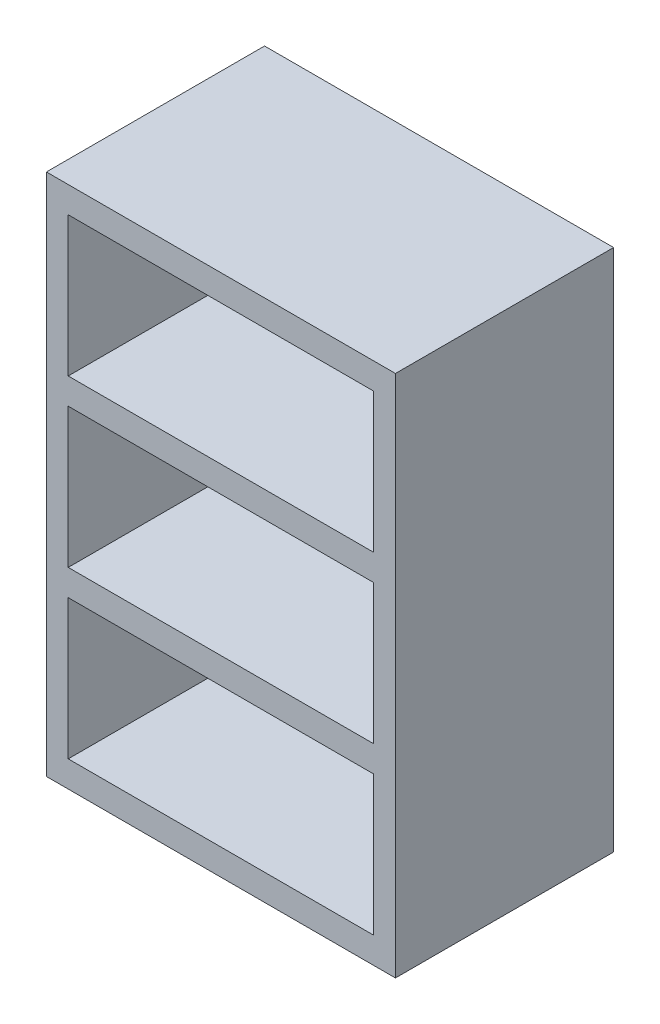
SolidWorks part; units mm, degrees
ref_plane "Front" through (0, 0, 0) normal (0, 0, 1) x (1, 0, 0)
ref_plane "Top" through (0, 0, 0) normal (0, 1, 0) x (1, 0, 0)
ref_plane "Right" through (0, 0, 0) normal (1, 0, 0) x (0, 0, -1)
sketch "Sketch1" plane through (0, 0, 0) normal (0, 0, 1) x (1, 0, 0)
  line L1 (-400, -600) -> (400, -600)
  line L2 (-400, -600) -> (-400, 600)
  line L3 (-400, 600) -> (400, 600)
  line L4 (400, -600) -> (400, 600)
  line L5 (-400, -600) -> (400, 600) construction
  line L6 (-400, 600) -> (400, -600) construction
  point P0 (0, 0)
  dimension "D1" = 1200
  dimension "D2" = 800
extrude "Boss-Extrude1" add sketch "Sketch1" along normal blind 500
sketch "Sketch2" plane through (0, 0, 500) normal (0, 0, 1) x (1, 0, 0)
  line L0 (400, 600) -> (-400, 600) construction
  line L5 (-350, 540) -> (350, 540)
  line L6 (-350, 540) -> (-350, 220)
  line L7 (-350, 220) -> (350, 220)
  line L8 (350, 540) -> (350, 220)
  line L9 (-350, 160) -> (350, 160)
  line L10 (-350, 160) -> (-350, -160)
  line L11 (-350, -160) -> (350, -160)
  line L12 (350, 160) -> (350, -160)
  line L13 (-350, -220) -> (350, -220)
  line L14 (-350, -220) -> (-350, -540)
  line L15 (-350, -540) -> (350, -540)
  line L16 (350, -220) -> (350, -540)
  line L17 (-400, -600) -> (400, -600) construction
  line L18 (-400, 600) -> (-400, -600) construction
  line L19 (400, -600) -> (400, 600) construction
  point P16 (-350, 380)
  dimension "D1" = 60
  dimension "D2" = 60
  dimension "D3" = 60
  dimension "D4" = 60
  dimension "D5" = 320
  dimension "D6" = 320
  dimension "D7" = 50
  dimension "D8" = 50
  dimension "D9" = 50
  dimension "D10" = 50
  dimension "D11" = 50
  dimension "D12" = 50
extrude "Cut-Extrude1" cut sketch "Sketch2" against normal blind 400
